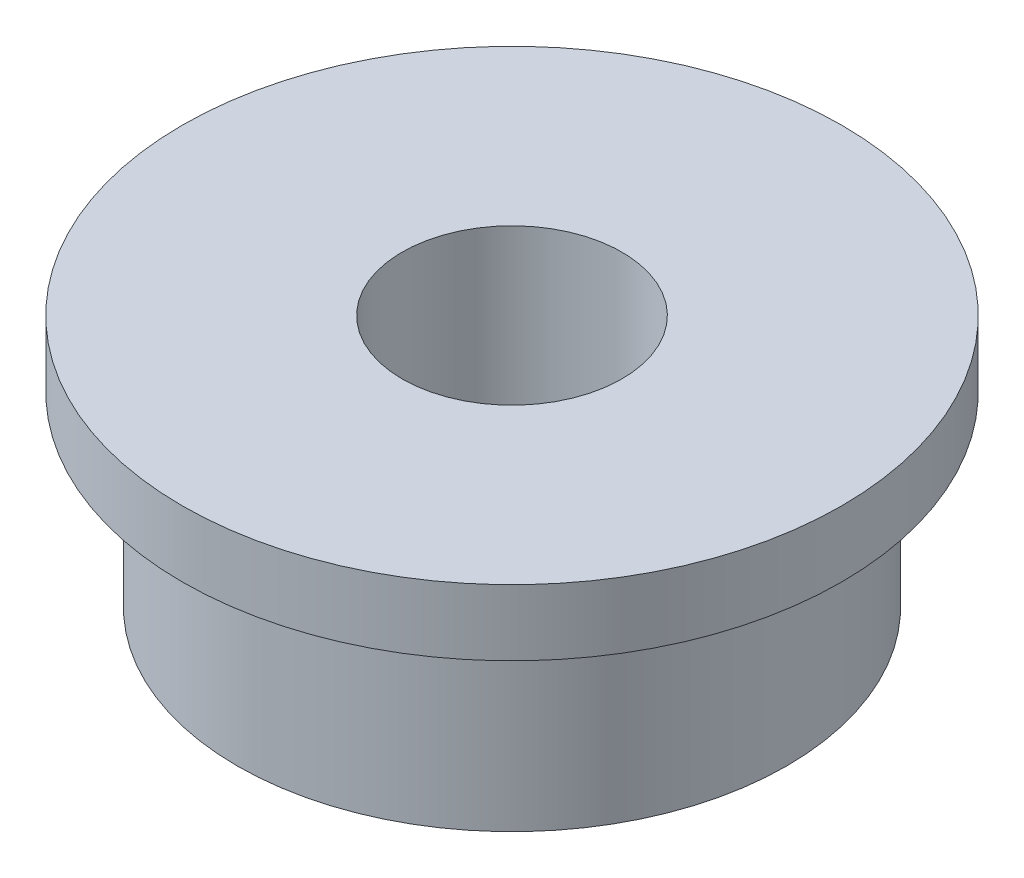
SolidWorks part; units mm, degrees
ref_plane "前视基准面" through (0, 0, 0) normal (0, 0, 1) x (1, 0, 0)
ref_plane "上视基准面" through (0, 0, 0) normal (0, 1, 0) x (1, 0, 0)
ref_plane "右视基准面" through (0, 0, 0) normal (1, 0, 0) x (0, 0, -1)
other "Configuration Table"
sketch "草图1" plane through (0, 0, 0) normal (0, 1, 0) x (1, 0, 0)
  circle A0 centre (0, 0) radius 1
  circle A1 centre (0, 0) radius 2.5
  dimension "D1" = 2
  dimension "D2" = 5
extrude "凸台-拉伸1" add sketch "草图1" along normal blind 2.3
sketch "草图2" plane through (0, 2.3, 0) normal (0, 1, 0) x (1, 0, 0)
  circle A0 centre (0, 0) radius 3
  circle A1 centre (0, 0) radius 1
  dimension "D1" = 6
extrude "凸台-拉伸2" add sketch "草图2" against normal blind 0.6
